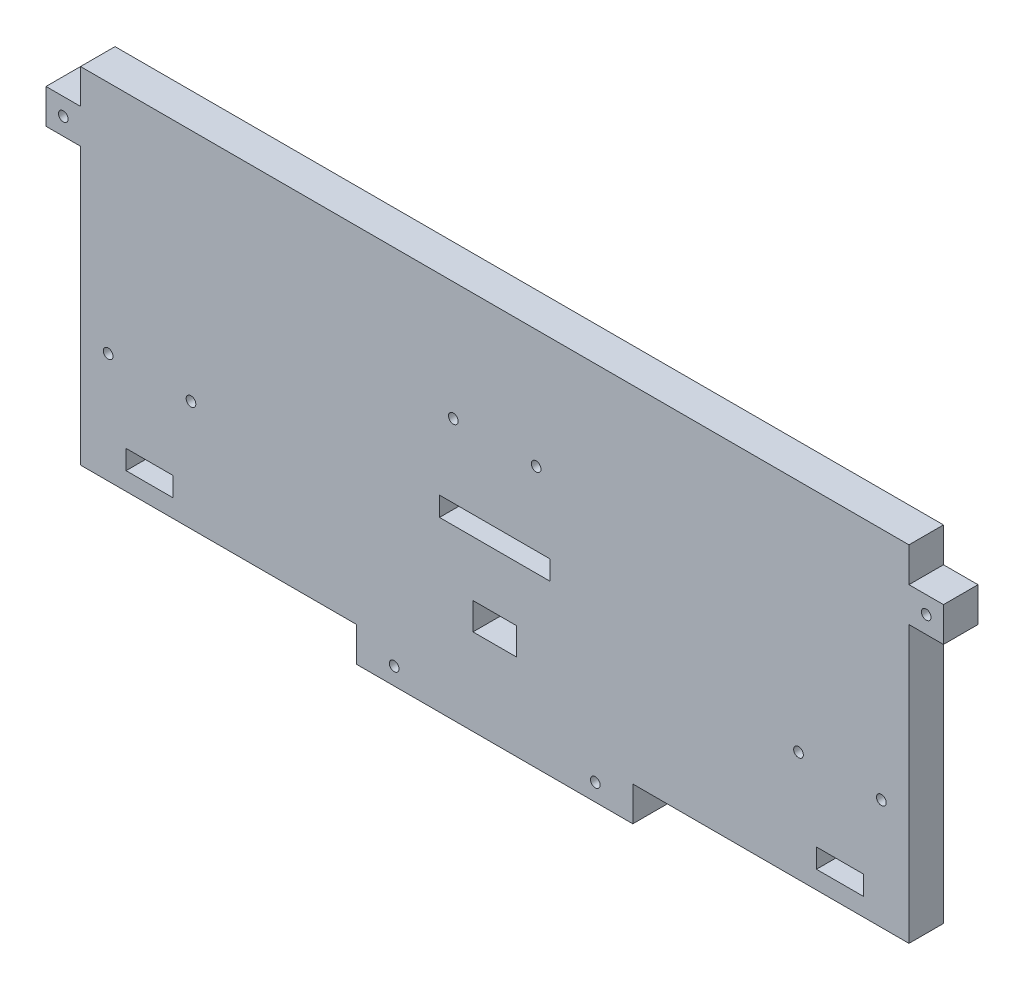
SolidWorks part; units mm, degrees
ref_plane "Front Plane" through (0, 0, 0) normal (0, 0, 1) x (1, 0, 0)
ref_plane "Top Plane" through (0, 0, 0) normal (0, 1, 0) x (1, 0, 0)
ref_plane "Right Plane" through (0, 0, 0) normal (1, 0, 0) x (0, 0, -1)
sketch "Sketch1" plane through (0, 0, 0) normal (0, 0, 1) x (1, 0, 0)
  line L0 (-4.0051, -10.0637) -> (-4.0051, 0.0963)
  line L1 (-80.2051, 38.9113) -> (-4.0051, 38.9113)
  line L2 (-80.2051, 38.9113) -> (-80.2051, 32.5613)
  line L3 (-80.2051, -24.5887) -> (-29.4051, -24.5887)
  line L4 (-4.0051, -10.0637) -> (-8.0051, -10.0637)
  line L5 (-80.2051, 32.5613) -> (-86.5551, 32.5613)
  line L6 (-4.0051, 3.6523) -> (-4.0051, 38.9113)
  line L7 (-80.2051, 26.2113) -> (-86.5551, 26.2113)
  line L8 (-86.5551, 32.5613) -> (-86.5551, 26.2113)
  line L9 (-4.0051, -15.0637) -> (-8.0051, -15.0637)
  line L10 (-8.0051, -10.0637) -> (-8.0051, -15.0637)
  line L11 (-63.1871, -17.7307) -> (-71.8231, -17.7307)
  line L12 (-80.2051, 26.2113) -> (-80.2051, -24.5887)
  line L13 (-4.0051, -30.9387) -> (-4.0051, -15.0637)
  line L14 (-29.4051, -24.5887) -> (-29.4051, -30.9387)
  line L15 (-29.4051, -30.9387) -> (-4.0051, -30.9387)
  line L16 (-63.1871, -17.7307) -> (-63.1871, -21.2867)
  line L17 (-63.1871, -21.2867) -> (-71.8231, -21.2867)
  line L18 (-71.8231, -17.7307) -> (-71.8231, -21.2867)
  line L19 (-4.0051, 0.0963) -> (-14.1651, 0.0963)
  line L21 (-4.0051, 3.6523) -> (-14.1651, 3.6523)
  line L22 (-14.1651, 0.0963) -> (-14.1651, 3.6523)
  circle A0 centre (-83.3801, 29.3863) radius 0.889
  circle A1 centre (-75.1251, -4.2687) radius 0.889
  circle A2 centre (-22.5051, -27.7637) radius 0.889
  circle A3 centre (-59.8851, -4.2687) radius 0.889
  circle A4 centre (-11.6251, 17.1143) radius 0.889
  dimension "D12" = 6.35
  dimension "D13" = 1.778
  dimension "D14" = 15.24
  dimension "D15" = 20.32
  dimension "D16" = 5.08
  dimension "D17" = 8.636
  dimension "D24" = 1.778
  dimension "D25" = 1.778
  dimension "D26" = 1.778
  dimension "D27" = 7.62
  dimension "D28" = 13.462
  dimension "D2" = 76.2
  dimension "D3" = 6.35
  dimension "D4" = 6.35
  dimension "D5" = 25.4
  dimension "D6" = 15.875
  dimension "D7" = 6.35
  dimension "D8" = 50.8
  dimension "D9" = 50.8
  dimension "D10" = 4
  dimension "D11" = 5
  dimension "D18" = 3.302
  dimension "D19" = 3.556
  dimension "D20" = 13.462
  dimension "D21" = 10.16
  dimension "D22" = 3.556
  dimension "D23" = 10.16
extrude "Boss-Extrude1" add sketch "Sketch1" along normal blind 6.35
mirror "Mirror1" about plane through (-4.0051, -10.0637, 6.35) normal (-1, 0, 0) of "Boss-Extrude1"
